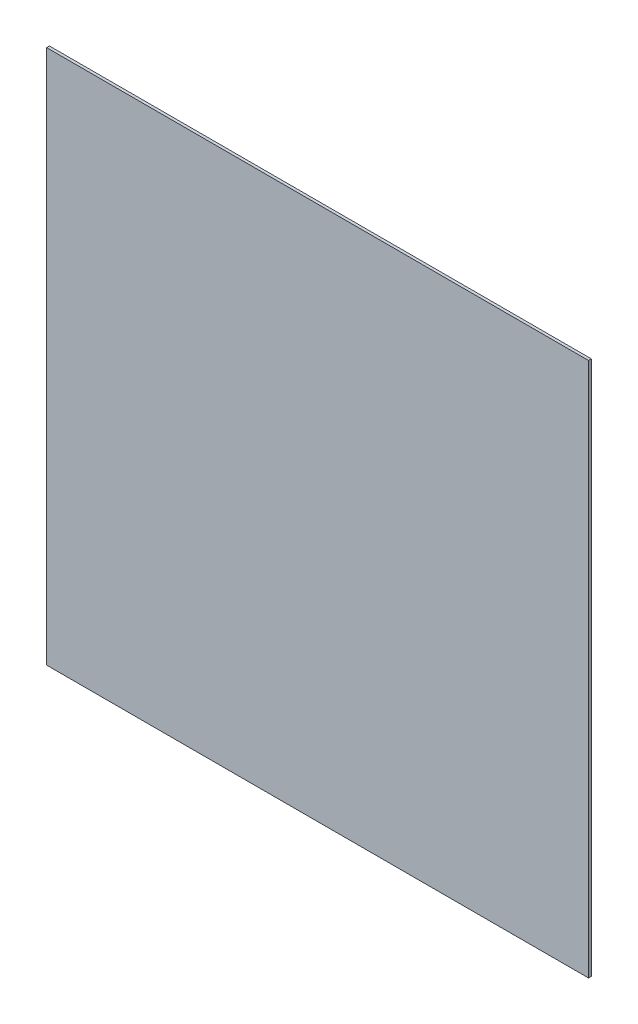
SolidWorks part; units mm, degrees
material "ABS"
ref_plane "Front Plane" through (0, 0, 0) normal (0, 0, 1) x (1, 0, 0)
ref_plane "Top Plane" through (0, 0, 0) normal (0, 1, 0) x (1, 0, 0)
ref_plane "Right Plane" through (0, 0, 0) normal (1, 0, 0) x (0, 0, -1)
sketch "Sketch1" plane through (0, 0, 0) normal (0, 0, 1) x (1, 0, 0)
  line L0 (0, 380) -> (0, 0) construction
  line L1 (-385, 380) -> (385, 380)
  line L2 (-385, 380) -> (-385, -380)
  line L3 (-385, -380) -> (385, -380)
  line L4 (385, 380) -> (385, -380)
  line L5 (0, 0) -> (0, -380) construction
  dimension "D1" = 760
  dimension "D2" = 770
extrude "Boss-Extrude1" add sketch "Sketch1" along normal blind 4
